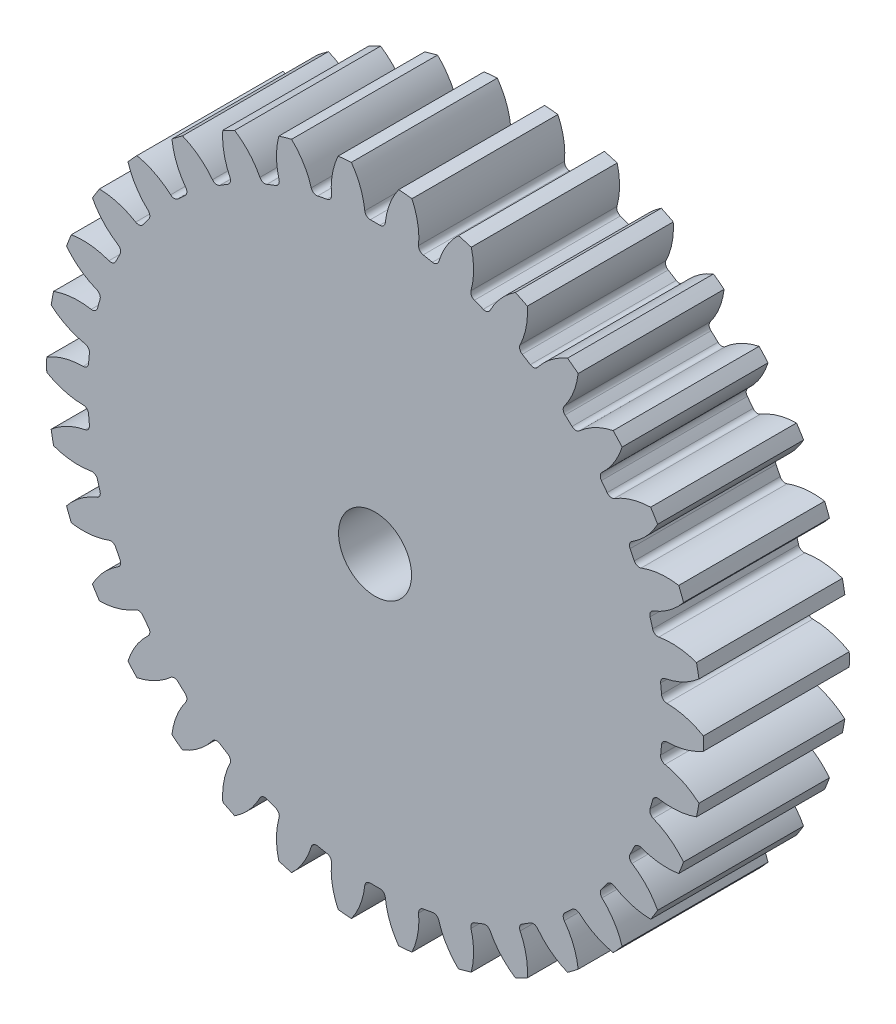
SolidWorks part; units mm, degrees
ref_plane "Ön Düzlem" through (0, 0, 0) normal (0, 0, 1) x (1, 0, 0)
ref_plane "Üst Düzlem" through (0, 0, 0) normal (0, 1, 0) x (1, 0, 0)
ref_plane "Sağ Düzlem" through (0, 0, 0) normal (1, 0, 0) x (0, 0, -1)
sketch "Çizim1" plane through (0, 0, 0) normal (0, 0, 1) x (1, 0, 0)
  circle A0 centre (0, 0) radius 34
  circle A1 centre (0, 0) radius 36
  circle A2 centre (0, 0) radius 31.5
  dimension "D1" = 68
  dimension "D2" = 72
  dimension "D3" = 63
extrude "Yükseklik-Ekstrüzyon1" add sketch "Çizim1" along normal mid plane 16 contours A1
sketch "Çizim2" plane through (0, 0, 8) normal (0, 0, 1) x (1, 0, 0)
  line L0 (0, 0) -> (0, 36) construction
  line L1 (-1.5702, 33.9637) -> (1.5702, 33.9637) construction
  line L2 (0, 29.6495) -> (-2.641, 36.9056) construction
  line L3 (0, 0) -> (-1.0881, 31.4812) construction
  line L4 (0, 0) -> (3.3217, 35.8464) construction
  line L5 (1.5702, 33.9637) -> (4.6973, 33.674) construction
  circle A0 centre (0, 0) radius 36 construction
  arc A1 (-3.3825, 36.8451) -> (-1.0881, 31.4812) centre (-9.1572, 31.2023) cw
  arc A2 (3.3825, 36.8451) -> (1.0881, 31.4812) centre (9.1572, 31.2023) ccw
  circle A3 centre (0, 0) radius 31.5 construction
  arc A4 (1.0881, 31.4812) -> (-1.0881, 31.4812) centre (0, 0) ccw
  circle A5 centre (0, 0) radius 34 construction
  circle A6 centre (0, 0) radius 36 construction
  circle A7 centre (0, 0) radius 37
  arc A8 (3.3825, 36.8451) -> (-3.3825, 36.8451) centre (0, 0) ccw
  dimension "D2" = 20
  dimension "D3" = 5.294
  dimension "D1" = 1
extrude "Kes-Ekstrüzyon1" cut sketch "Çizim2" against normal blind 16
fillet "Radyus1" radius 0.6 2 edges at (1.0881, 31.4812, 0) (-1.0881, 31.4812, 0)
pattern_circular "Dairesel Kaplama1" count 34 over 360 about axis through (0, 0, 0) along (0, 0, 1) of "Radyus1", "Kes-Ekstrüzyon1"
sketch "Sketch5" plane through (0, 0, 8) normal (0, 0, 1) x (1, 0, 0)
  circle A0 centre (0, 0) radius 4
  dimension "D1" = 8
extrude "Cut-Extrude1" cut sketch "Sketch5" against normal blind 54
sketch "Sketch6" plane through (0, 0, -8) normal (0, 0, -1) x (-1, 0, 0)
  circle A0 centre (0, 0) radius 4
  circle A1 centre (0, 0) radius 7.5
  dimension "D1" = 8
  dimension "D2" = 15
extrude "Boss-Extrude1" add sketch "Sketch6" along normal blind 10
sketch "Sketch7" plane through (0, 0, 0) normal (0, 1, 0) x (1, 0, 0)
  line L0 (0, 0) -> (0, 18) construction
  line L1 (7.5, 18) -> (-7.5, 18) construction
  circle A0 centre (0, 13) radius 2.1
  dimension "D1" = 4.2
  dimension "D2" = 5
extrude "Cut-Extrude3" cut sketch "Sketch7" against normal through all both and the other way through all
fillet "Fillet1" radius 1 1 edges at (-7.5, 0, -18)
equation "\"m\"= 2mm'modül"
equation "\"z\"= 34'diş sayısı"
equation "\"D1@Çizim1\"=\"m\"*\"z\""
equation "\"D2@Çizim1\"=\"m\"*(\"z\"+2)"
equation "\"D3@Çizim1\"=\"m\"*(\"z\"-2.5)"
equation "\"D1@Yükseklik-Ekstrüzyon1\"=\"m\"*8"
equation "\"D3@Çizim2\"=180/\"z\""
equation "\"D1\"= \"m\" * 8"
equation "\"D1@Radyus1\"=\"m\"*0.3"
equation "\"D1@Dairesel Kaplama1\"=\"z\""
equation "\"D1@Kes-Ekstrüzyon1\"=\"m\"*8"
